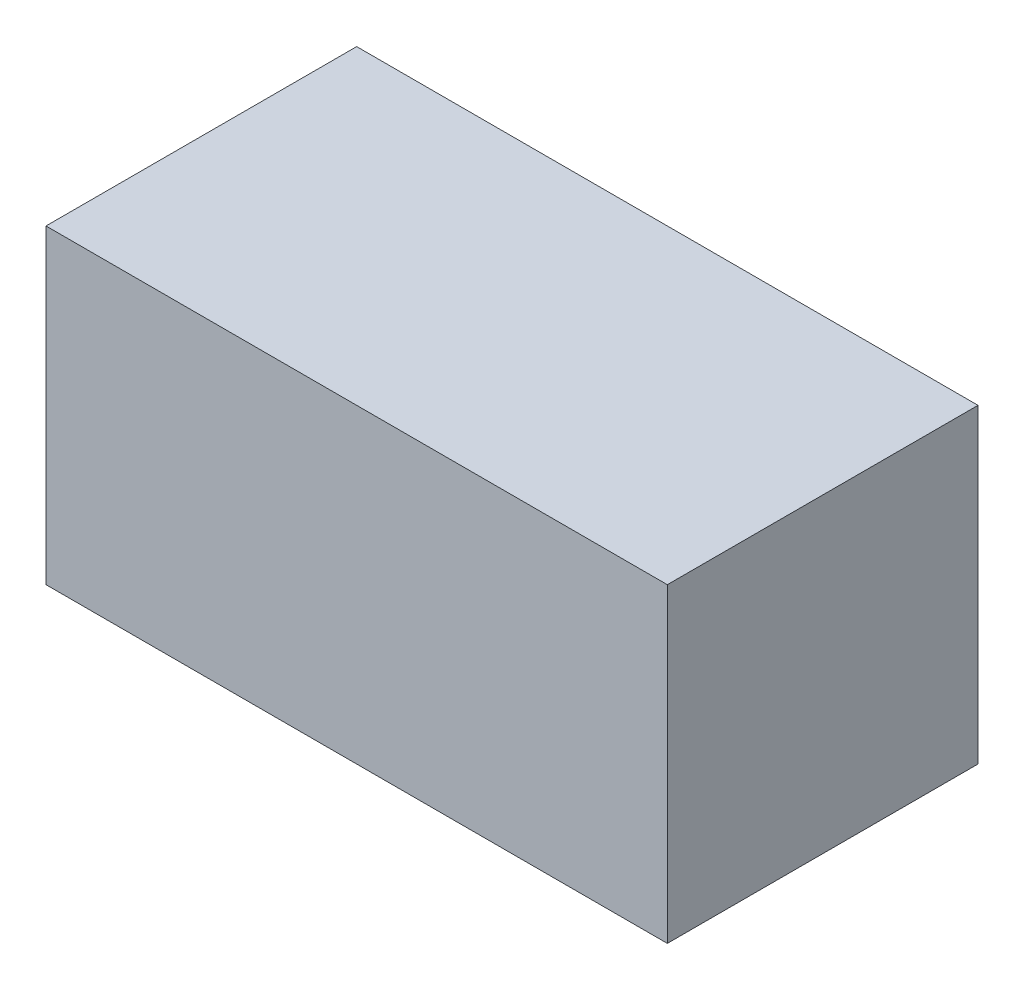
SolidWorks part; units mm, degrees
ref_plane "Front Plane" through (0, 0, 0) normal (0, 0, 1) x (1, 0, 0)
ref_plane "Top Plane" through (0, 0, 0) normal (0, 1, 0) x (1, 0, 0)
ref_plane "Right Plane" through (0, 0, 0) normal (1, 0, 0) x (0, 0, -1)
sketch "Sketch1" plane through (0, 0, 0) normal (0, 0, 1) x (1, 0, 0)
  line L1 (0, 0) -> (20, 0)
  line L2 (0, 0) -> (0, 10)
  line L3 (0, 10) -> (20, 10)
  line L4 (20, 0) -> (20, 10)
  dimension "D1" = 10
  dimension "D2" = 20
extrude "Boss-Extrude1" add sketch "Sketch1" along normal blind 10
